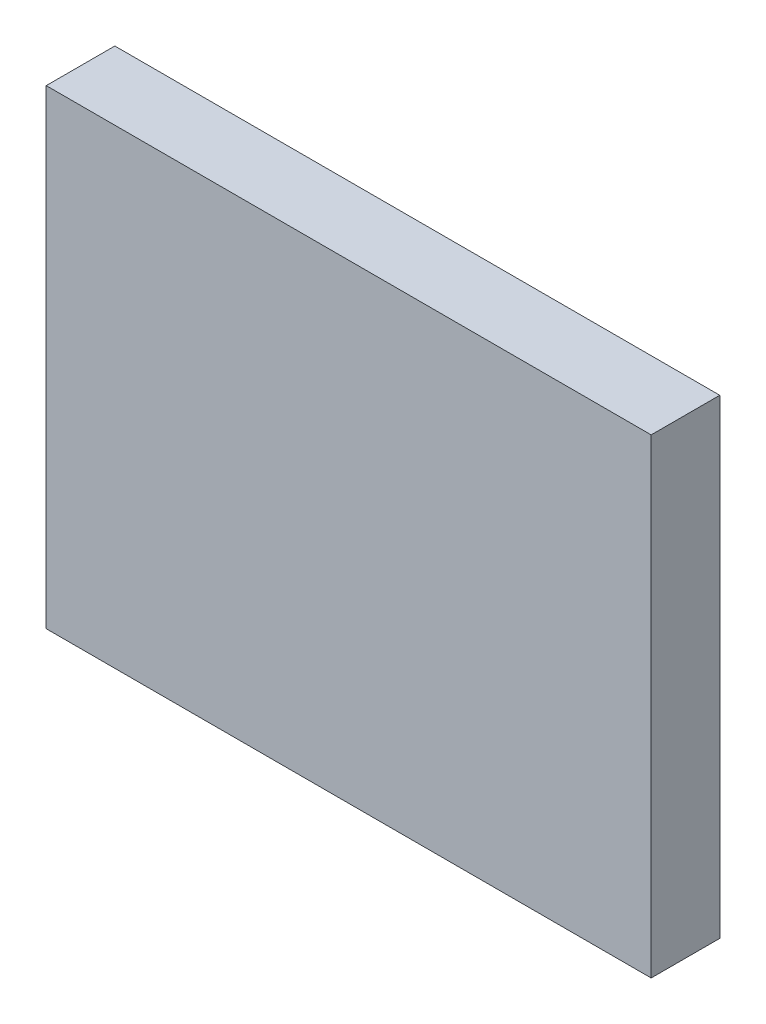
SolidWorks part; units mm, degrees
ref_plane "Front Plane" through (0, 0, 0) normal (0, 0, 1) x (1, 0, 0)
ref_plane "Top Plane" through (0, 0, 0) normal (0, 1, 0) x (1, 0, 0)
ref_plane "Right Plane" through (0, 0, 0) normal (1, 0, 0) x (0, 0, -1)
sketch "Sketch1" plane through (0, 0, 0) normal (0, 0, 1) x (1, 0, 0)
  line L0 (49.65, -40) -> (49.65, 40) construction
  line L1 (-6.35, 40) -> (49.65, 40)
  line L2 (-6.35, 40) -> (-6.35, -3.5426)
  line L3 (-6.35, -3.5426) -> (49.65, -3.5426)
  line L4 (49.65, 40) -> (49.65, -3.5426)
extrude "Boss-Extrude1" add sketch "Sketch1" along normal blind 6.35
